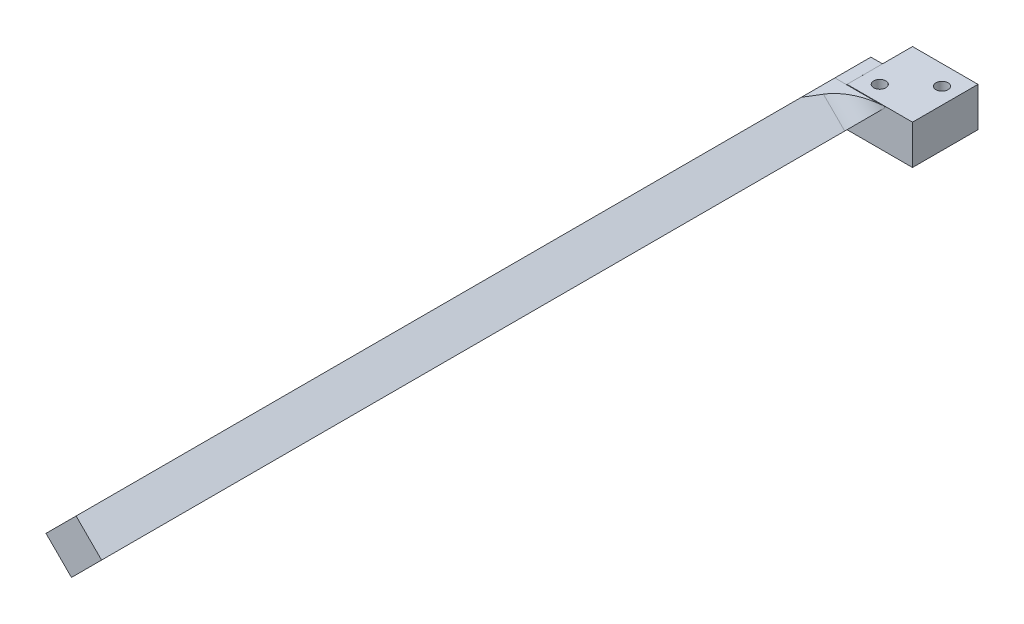
SolidWorks part; units mm, degrees
ref_plane "Alzado" through (0, 0, 0) normal (0, 0, 1) x (1, 0, 0)
ref_plane "Planta" through (0, 0, 0) normal (0, 1, 0) x (1, 0, 0)
ref_plane "Vista lateral" through (0, 0, 0) normal (1, 0, 0) x (0, 0, -1)
sketch "Croquis1" plane through (0, 0, 0) normal (0, 0, 1) x (1, 0, 0)
  line L1 (-47.0808, -210.5199) -> (-27.0808, -210.5199)
  line L2 (-47.0808, -210.5199) -> (-47.0808, -222.5199)
  line L3 (-47.0808, -222.5199) -> (-27.0808, -222.5199)
  line L4 (-27.0808, -210.5199) -> (-27.0808, -222.5199)
extrude "Saliente-Extruir1" add sketch "Croquis1" along normal blind 20
sketch "Croquis2" plane through (0, -222.5199, 0) normal (0, -1, 0) x (1, 0, 0)
  circle A0 centre (-42.0808, 15) radius 1.85
  circle A1 centre (-32.0808, 6) radius 1.85
extrude "Cortar-Extruir1" cut sketch "Croquis2" against normal blind 20
sketch "Croquis4" plane through (-47.0808, 0, 0) normal (-1, 0, 0) x (0, 0, 1)
  circle A0 centre (3.719, -216.7083) radius 1.3888
extrude "Cortar-Extruir2" cut sketch "Croquis4" against normal blind 1
sketch "Croquis5" plane through (87.7196, -87.7196, -86.9757) normal (-0.7071, 0.7071, 0) x (0, 0, -1)
  line L0 (-286.9757, 190.0873) -> (-286.9757, 239.2798) construction
  line L1 (-286.9757, 258.0091) -> (-286.9757, 271.0091)
  line L2 (-106.9757, 168.0091) -> (-86.9757, 168.0091) construction
  line L3 (-286.9757, 271.0091) -> (-101.1303, 190.6375)
  line L5 (-101.1303, 190.6375) -> (-107.1303, 190.6375)
  line L6 (-107.1303, 190.6375) -> (-107.1303, 173.6375)
  line L7 (-113.1833, 182.85) -> (-286.9757, 258.0091)
  line L9 (-106.9757, 190.6365) -> (-86.9757, 190.6365) construction
  arc A0 (-107.1303, 173.6375) -> (-113.1833, 182.85) centre (-117.1674, 173.6375) ccw
  dimension "D1" = 200
  dimension "D2" = 13
  dimension "D3" = 90
  dimension "D4" = 17
  dimension "D5" = 6
  dimension "D6" = 0.001
extrude "Saliente-Extruir11" add sketch "Croquis5" along normal blind 11 separate body
sketch "Croquis6" plane through (0, 0, 20.1547) normal (0, 0, -1) x (-1, 0, 0)
  line L0 (47.0818, -222.5203) -> (54.8597, -214.7424)
  line L1 (54.8597, -214.7424) -> (50.6371, -210.5199)
  line L2 (42.8389, -202.7216) -> (54.8597, -214.7424) construction
  line L3 (50.6371, -210.5199) -> (47.0818, -210.5199)
  line L4 (47.0818, -210.5199) -> (47.0818, -222.5203)
  line L5 (54.8597, -214.7424) -> (47.0815, -222.5206) construction
  line L6 (47.0808, -210.5199) -> (47.0808, -222.5199) construction
  line L7 (47.0808, -210.5199) -> (47.0808, -222.5199)
  dimension "D1" = 0.001
extrude "Saliente-Extruir13" add sketch "Croquis6" along normal blind 11 contours L3 L4 L0 L1
sketch "Croquis7" plane through (0, 0, 20.1547) normal (0, 0, -1) x (-1, 0, 0)
  line L0 (50.637, -210.5198) -> (42.8389, -202.7216)
  line L1 (42.8389, -202.7216) -> (50.6371, -210.5199) construction
  line L2 (42.8389, -202.7216) -> (35.0407, -210.5198)
  line L3 (42.8389, -202.7216) -> (35.0607, -210.4998) construction
  line L4 (35.0407, -210.5198) -> (50.637, -210.5198)
  line L5 (27.0808, -210.5199) -> (47.0808, -210.5199) construction
  line L6 (27.0808, -210.5199) -> (47.0808, -210.5199)
  line M6 (50.6371, -210.5199) -> (42.8389, -202.7216)
  line M7 (42.8389, -202.7216) -> (35.0607, -210.4998)
  line M8 (35.0607, -210.4998) -> (47.0815, -222.5206)
  dimension "D1" = 0.0001
extrude "Cortar-Extruir3" cut sketch "Croquis7" against normal blind 11 contours L4 M8 M6 M7
